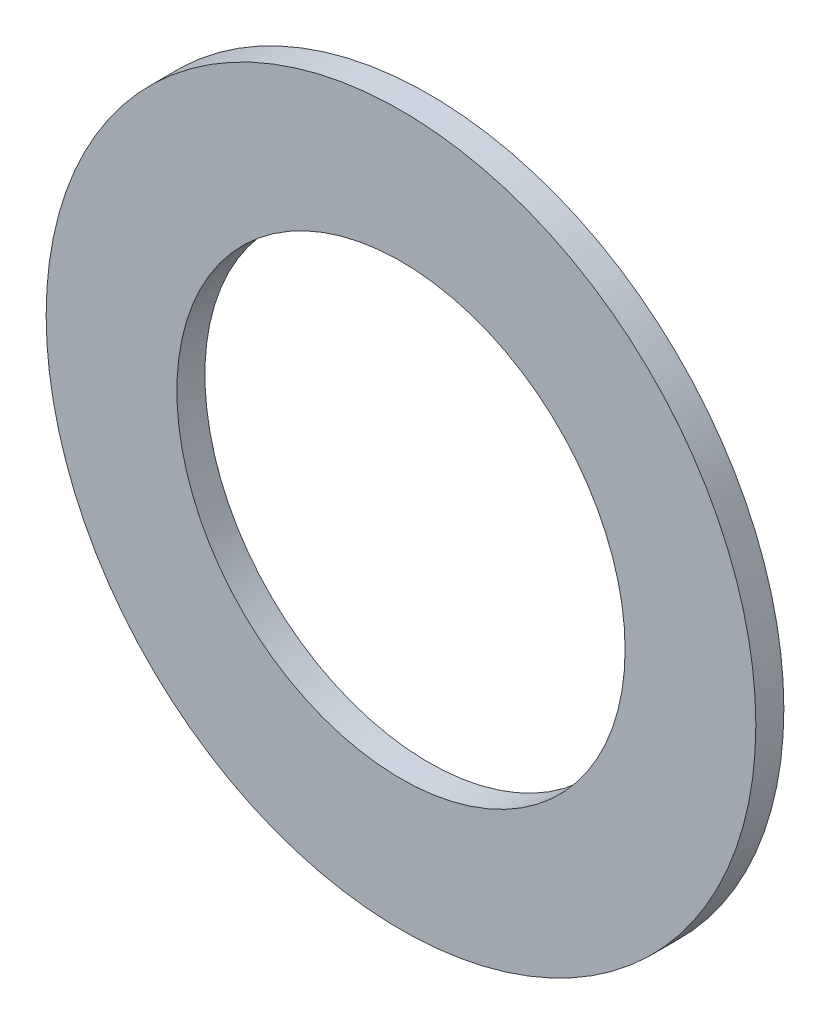
SolidWorks part; units mm, degrees
ref_plane "Front Plane" through (0, 0, 0) normal (0, 0, 1) x (1, 0, 0)
ref_plane "Top Plane" through (0, 0, 0) normal (0, 1, 0) x (1, 0, 0)
ref_plane "Right Plane" through (0, 0, 0) normal (1, 0, 0) x (0, 0, -1)
sketch "Sketch1" plane through (0, 0, 0) normal (0, 0, 1) x (1, 0, 0)
  circle A0 centre (0, 0) radius 12
  circle A1 centre (0, 0) radius 19
  dimension "D1" = 24
  dimension "D2" = 38
extrude "Boss-Extrude1" add sketch "Sketch1" along normal blind 1.5
